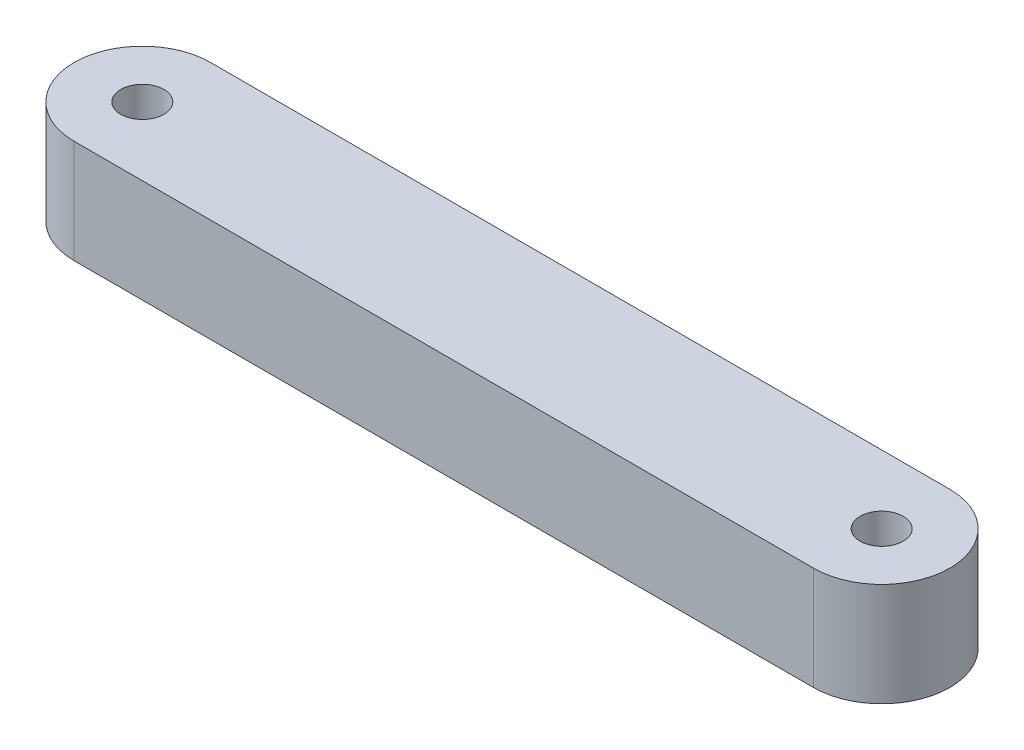
SolidWorks part; units mm, degrees
ref_plane "Front Plane" through (0, 0, 0) normal (0, 0, 1) x (1, 0, 0)
ref_plane "Top Plane" through (0, 0, 0) normal (0, 1, 0) x (1, 0, 0)
ref_plane "Right Plane" through (0, 0, 0) normal (1, 0, 0) x (0, 0, -1)
sketch "Sketch1" plane through (0, 0, 0) normal (0, 1, 0) x (1, 0, 0)
  line L0 (0, 0) -> (90.805, 0) construction
  line L1 (0, 8.382) -> (90.805, 8.382)
  line L2 (0, -8.382) -> (90.805, -8.382)
  arc A0 (0, 8.382) -> (0, -8.382) centre (0, 0) ccw
  arc A1 (90.805, -8.382) -> (90.805, 8.382) centre (90.805, 0) ccw
  circle A2 centre (0, 0) radius 2.65
  circle A3 centre (90.805, 0) radius 2.65
  point P3 (45.4025, 0)
  dimension "D3" = 5.3
  dimension "D4" = 5.3
  dimension "D1" = 90.805
  dimension "D2" = 16.764
extrude "Boss-Extrude1" add sketch "Sketch1" along normal blind 12.7
